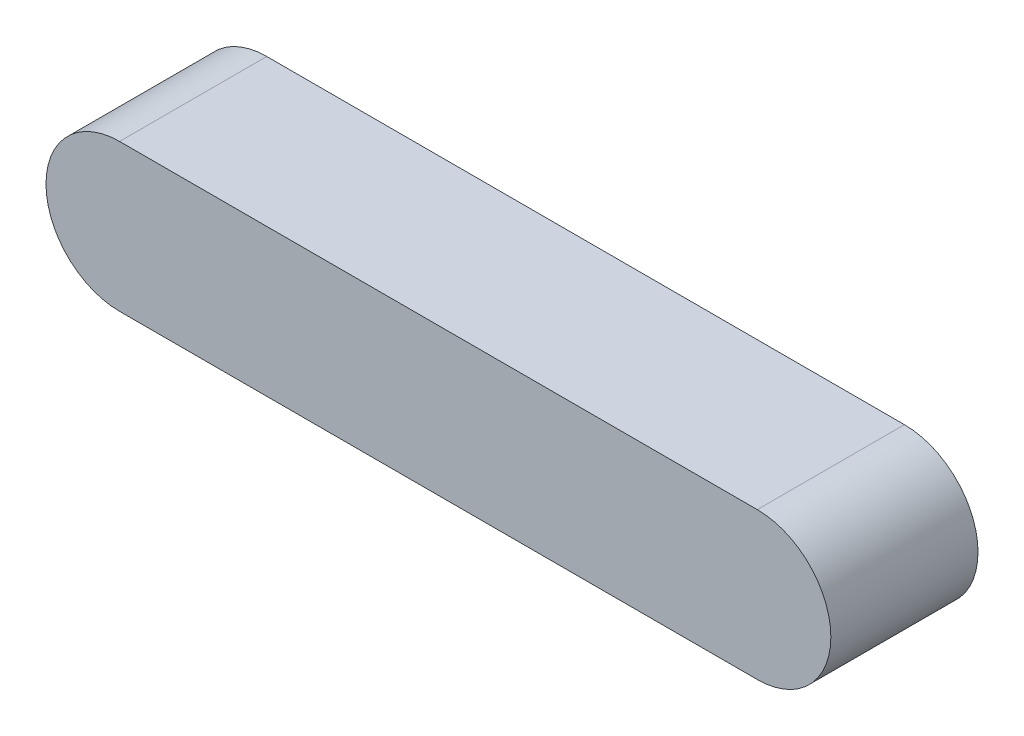
SolidWorks part; units mm, degrees
ref_plane "Plan de face" through (0, 0, 0) normal (0, 0, 1) x (1, 0, 0)
ref_plane "Plan de dessus" through (0, 0, 0) normal (0, 1, 0) x (1, 0, 0)
ref_plane "Plan de droite" through (0, 0, 0) normal (1, 0, 0) x (0, 0, -1)
sketch "Esquisse1" plane through (0, 0, 0) normal (0, 0, 1) x (1, 0, 0)
  line L0 (0, 0) -> (26, 0)
  line L1 (26, -6) -> (0, -6)
  arc A0 (26, 0) -> (26, -6) centre (26, -3) cw
  arc A1 (0, -6) -> (0, 0) centre (0, -3) cw
  dimension "D1" = 6
  dimension "D2" = 26
extrude "Extrusion1" add sketch "Esquisse1" along normal blind 6
